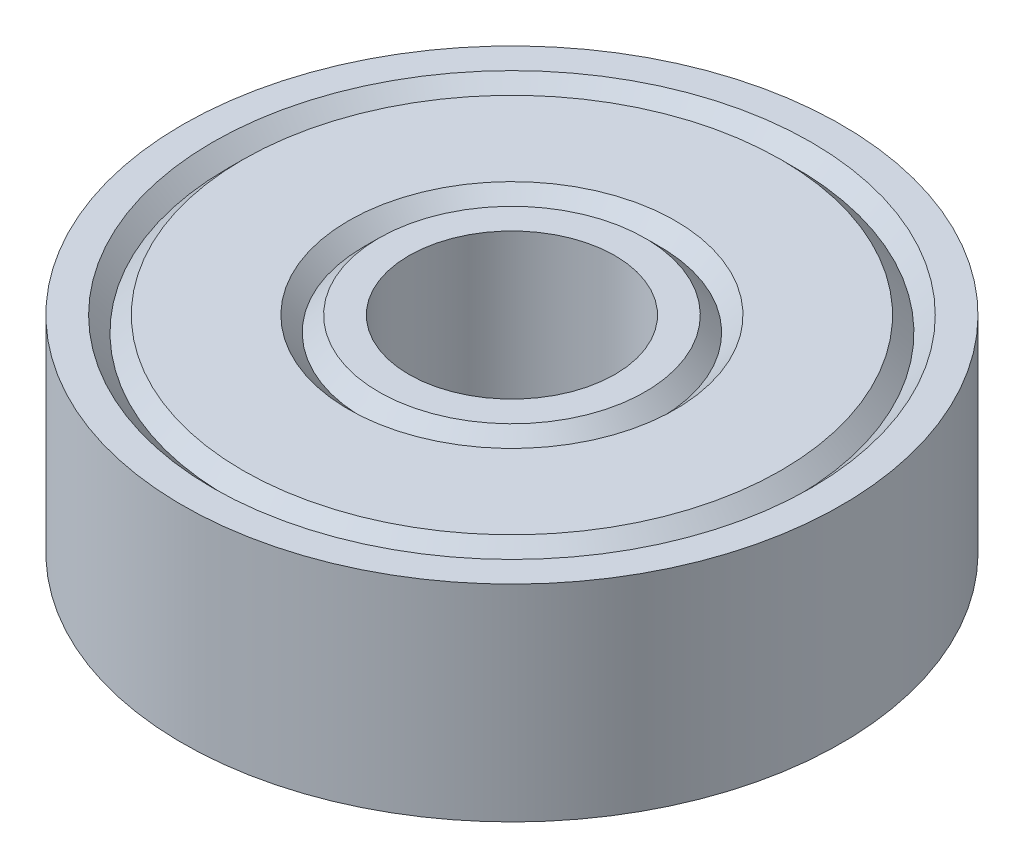
SolidWorks part; units mm, degrees
ref_plane "Front Plane" through (0, 0, 0) normal (0, 0, 1) x (1, 0, 0)
ref_plane "Top Plane" through (0, 0, 0) normal (0, 1, 0) x (1, 0, 0)
ref_plane "Right Plane" through (0, 0, 0) normal (1, 0, 0) x (0, 0, -1)
sketch "Sketch1" plane through (0, 0, 0) normal (0, 0, 1) x (1, 0, 0)
  line L0 (0, 2.5) -> (0, -2.5) construction
  line L1 (-2.5, 2.5) -> (-3.2333, 2.5)
  line L2 (-2.5, 2.5) -> (-2.5, -2.5)
  line L3 (-2.5, -2.5) -> (-3.2333, -2.5)
  line L4 (-8, 2.5) -> (-8, -2.5)
  line L5 (-7.2667, 2.5) -> (-6.9, 2.1333)
  line L6 (-6.9, 2.1333) -> (-6.5333, 2.5)
  line L7 (-3.9667, 2.5) -> (-3.6, 2.1333)
  line L8 (-3.6, 2.1333) -> (-3.2333, 2.5)
  line L9 (-7.2667, -2.5) -> (-6.9, -2.1333)
  line L10 (-6.9, -2.1333) -> (-6.5333, -2.5)
  line L11 (-3.9667, -2.5) -> (-3.6, -2.1333)
  line L12 (-3.6, -2.1333) -> (-3.2333, -2.5)
  line L13 (-3.9667, -2.5) -> (-6.5333, -2.5)
  line L14 (-7.2667, -2.5) -> (-8, -2.5)
  line L15 (-7.2667, 2.5) -> (-8, 2.5)
  line L16 (-3.9667, 2.5) -> (-6.5333, 2.5)
  line L17 (-6.9, 2.1333) -> (-3.6, 2.1333) construction
  line L18 (-6.9, 2.1333) -> (-6.9, -2.1333) construction
  line L19 (-3.6, -2.1333) -> (-6.9, -2.1333) construction
  line L20 (-3.6, 2.1333) -> (-3.6, -2.1333) construction
  line L21 (-6.9, 0) -> (-5.8, 0) construction
  line L22 (-3.2333, 2.5) -> (-3.9667, 2.5) construction
  line L23 (-5.8, 0) -> (-4.7, 0) construction
  line L24 (-6.9, 0) -> (-8, 0) construction
  line L25 (-4.7, 0) -> (-3.6, 0) construction
  line L26 (-3.6, 0) -> (-2.5, 0) construction
  dimension "D1" = 5
  dimension "D2" = 5
  dimension "D3" = 16
revolve "Revolve1" add sketch "Sketch1" angle 360 about L0
